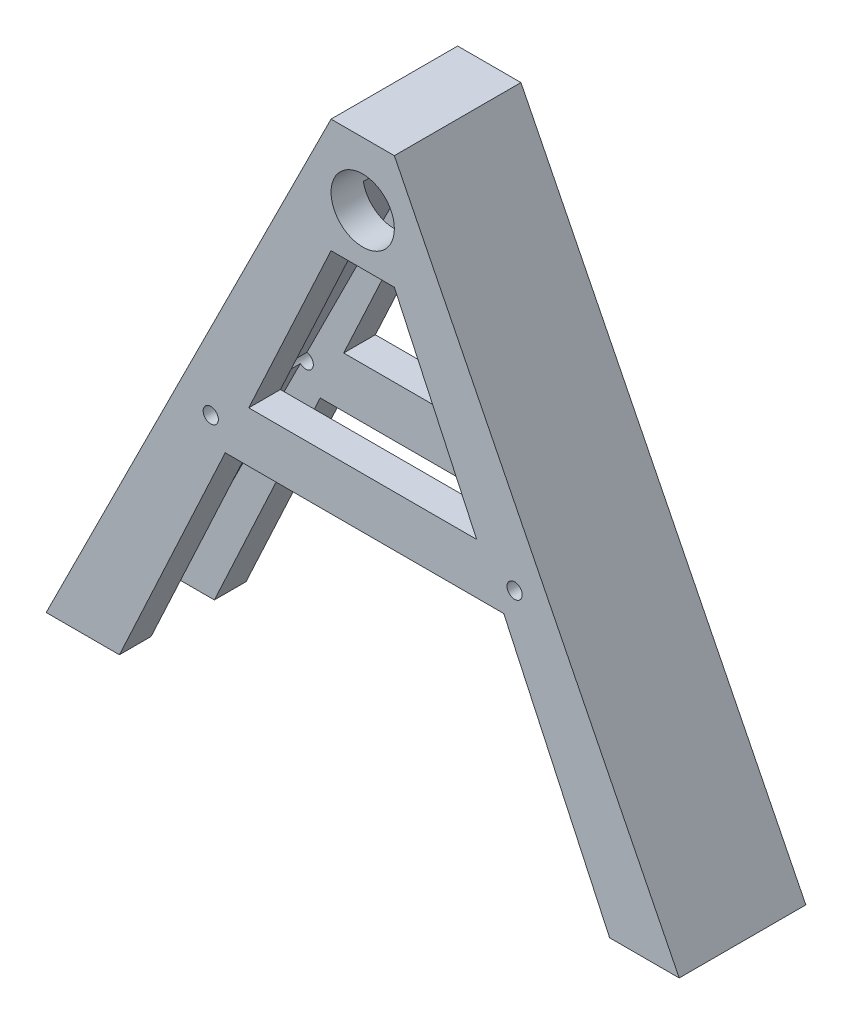
SolidWorks part; units mm, degrees
material "Cedar"
ref_plane "Front Plane" through (0, 0, 0) normal (0, 0, 1) x (1, 0, 0)
ref_plane "Top Plane" through (0, 0, 0) normal (0, 1, 0) x (1, 0, 0)
ref_plane "Right Plane" through (0, 0, 0) normal (1, 0, 0) x (0, 0, -1)
sketch "Sketch1" plane through (0, 0, 0) normal (0, 1, 0) x (1, 0, 0)
  line L1 (-63.5, -12.7) -> (63.5, -12.7)
  line L2 (-63.5, -12.7) -> (-63.5, 12.7)
  line L3 (-63.5, 12.7) -> (63.5, 12.7)
  line L4 (63.5, -12.7) -> (63.5, 12.7)
  line L5 (-63.5, -12.7) -> (63.5, 12.7) construction
  line L6 (-63.5, 12.7) -> (63.5, -12.7) construction
  point P0 (0, 0)
  dimension "D1" = 127
  dimension "D2" = 25.4
ref_plane "Plane2" through (0, 114.3, 0) normal (0, 1, 0) x (1, 0, 0)
sketch "Sketch2" plane through (0, 114.3, 0) normal (0, 1, 0) x (1, 0, 0)
  line L4 (-6.35, -12.7) -> (6.35, -12.7)
  line L9 (-6.35, -12.7) -> (-6.35, 12.7)
  line L13 (-6.35, 12.7) -> (6.35, 12.7)
  line L14 (6.35, -12.7) -> (6.35, 12.7)
  line L15 (-6.35, -12.7) -> (6.35, 12.7) construction
  line L16 (-6.35, 12.7) -> (6.35, -12.7) construction
  point P0 (0, 0)
  dimension "D1" = 25.4
  dimension "D2" = 12.7
loft "Loft1" add profiles "Sketch2", "Sketch1"
shell "Shell1" thickness 6.35
sketch "Sketch3" plane through (0, 0, 12.7) normal (0, 0, 1) x (1, 0, 0)
  line L1 (6.35, 91.44) -> (22.86, 55.88)
  line L2 (22.86, 55.88) -> (-22.86, 55.88)
  line L3 (-22.86, 55.88) -> (-6.35, 91.44)
  line L6 (28.3029, 45.72) -> (49.53, 0)
  line L7 (-63.5, 0) -> (63.5, 0) construction
  line L8 (49.53, 0) -> (-48.8043, 0)
  line L9 (-48.8043, 0) -> (-27.5771, 45.72)
  line L12 (-27.5771, 45.72) -> (28.3029, 45.72)
  line L13 (-6.35, 91.44) -> (6.35, 91.44)
  line L16 (0, 0) -> (0, 91.44) construction
  point P19 (0, 55.88)
  dimension "D1" = 45.72
  dimension "D2" = 35.56
  dimension "D3" = 12.7
  dimension "D4" = 45.72
  dimension "D6" = 10.16
  dimension "D7" = 55.88
extrude "Cut-Extrude1 Letter A" cut sketch "Sketch3" against normal through all
sketch "Sketch4" plane through (0, 0, 12.7) normal (0, 0, 1) x (1, 0, 0)
  circle A0 centre (0, 101.6) radius 6.35
  dimension "D1" = 12.7
  dimension "D2" = 101.6
extrude "Cut-Extrude2 Axle" cut sketch "Sketch4" against normal through all
scale "Scale1" scale about origin uniform scaling yes scale factor 0.5
sketch "Sketch5" plane through (0, 0, 6.35) normal (0, 0, 1) x (1, 0, 0)
  line L2 (0, 0) -> (0, 50.8) construction
  circle A2 centre (-15.24, 25.4) radius 0.762
  circle A3 centre (15.24, 25.4) radius 0.762
  dimension "D1" = 1.524
  dimension "D2" = 15.24
  dimension "D3" = 25.4
extrude "Cut-Extrude1" cut sketch "Sketch5" against normal through all
